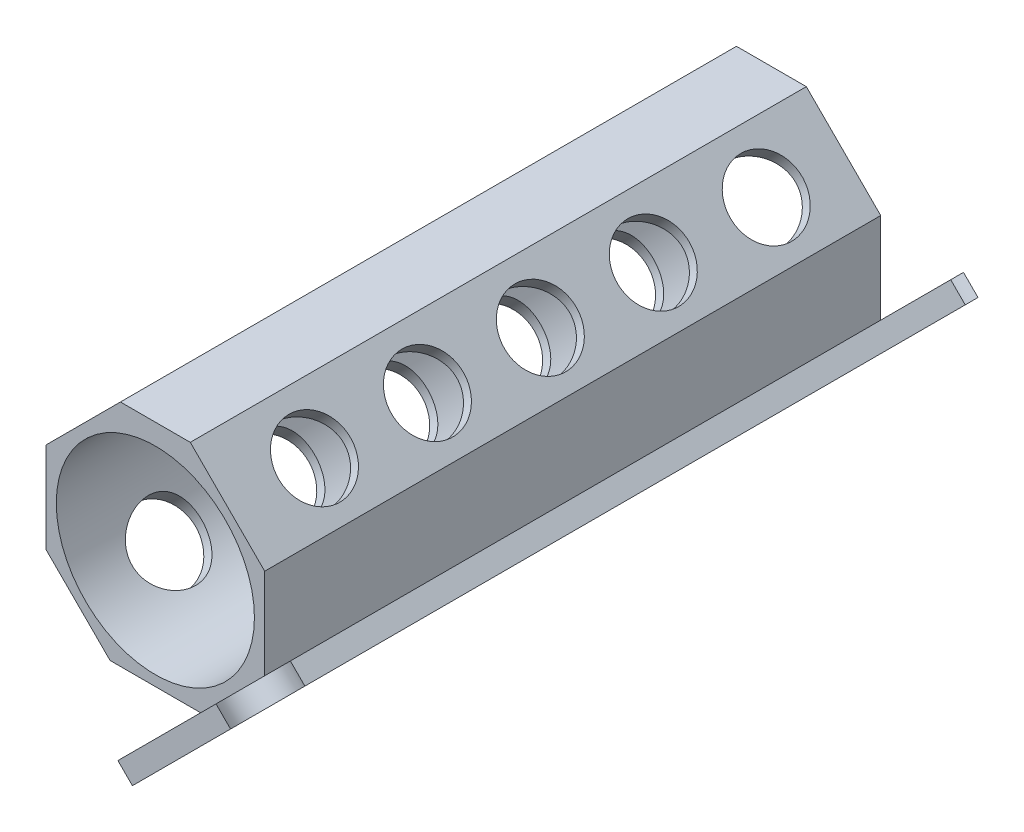
SolidWorks part; units mm, degrees
ref_plane "Ebene vorne" through (0, 0, 0) normal (1, 0, 0) x (0, 1, 0)
ref_plane "Ebene oben" through (0, 0, 0) normal (0, 0, 1) x (0, 1, 0)
ref_plane "Ebene rechts" through (0, 0, 0) normal (0, 1, 0) x (-1, 0, 0)
sketch "Skizze1" plane through (0, 0, 0) normal (0, 0, 1) x (0, 1, 0)
  line L0 (11.6589, 3.4025) -> (11.6589, -3.4025)
  line L13 (11.6589, 3.4025) -> (4.4114, 10.65)
  line L14 (4.4114, 10.65) -> (-4.4114, 10.65)
  line L15 (-4.4114, 10.65) -> (-10.65, 4.4114)
  line L16 (-10.65, 4.4114) -> (-10.65, -4.4114)
  line L17 (-10.65, -4.4114) -> (-4.4114, -10.65)
  line L18 (-4.4114, -10.65) -> (4.4114, -10.65)
  line L19 (4.4114, -10.65) -> (11.6589, -3.4025)
  line L29 (10.65, -1.6019) -> (10.65, 6.6409) [skipped]
  circle A0 centre (0, 0) radius 9.65
  circle A1 centre (0, 0) radius 10.65 construction
  dimension "D1" = 19.3
  dimension "D2" = 21.3
extrude "Aufsatz-Linear austragen1" add sketch "Skizze1" along normal blind 60
sketch "Skizze9" plane through (7.5307, 7.5307, 0) normal (0.7071, 0.7071, 0) x (-0.7071, 0.7071, 0)
  line L0 (0.7134, 60) -> (0.7134, 0) construction
  line L2 (-4.4114, 60) -> (5.8381, 60) construction
  line L3 (-4.4114, 0) -> (5.8381, 0) construction
  circle A0 centre (0.6135, 51.6) radius 3.5
  circle A1 centre (0.6135, 40.6) radius 3.5
  circle A2 centre (0.6135, 29.6) radius 3.5
  circle A3 centre (0.6135, 18.6) radius 3.5
  circle A4 centre (0.6135, 7.6) radius 3.5
  dimension "D1" = 7
  dimension "D2" = 5
extrude "Schnitt-Linear austragen8" cut sketch "Skizze9" against normal through all
sketch "Skizze13" plane through (7.5307, -7.5307, 0) normal (0.7071, -0.7071, 0) x (0.7071, 0.7071, 0)
  line L0 (0, 60) -> (0, 0) construction
  line L1 (-11, -6.4) -> (11, -6.4)
  line L2 (-11, -6.4) -> (-11, 66.4)
  line L3 (-11, 66.4) -> (11, 66.4)
  line L4 (11, -6.4) -> (11, 66.4)
  line L5 (-11, -6.4) -> (11, 66.4) construction
  line L6 (-11, 66.4) -> (11, -6.4) construction
  line L7 (-4.4114, 60) -> (4.4114, 60) construction
  point P0 (0, 30)
  point P11 (0, 30)
  dimension "D1" = 22
  dimension "D2" = 72.8
extrude "Aufsatz-Linear austragen2" add sketch "Skizze13" along normal blind 2
sketch "Skizze14" plane through (8.9449, -8.9449, 0) normal (0.7071, -0.7071, 0) x (0.7071, 0.7071, 0)
  circle A0 centre (8.88, 64.28) radius 3
  circle A2 centre (-8.88, -4.28) radius 3
  circle A3 centre (8.88, -4.28) radius 3
  circle A4 centre (-8.88, 64.28) radius 3
  dimension "D1" = 6
  dimension "D2" = 2.12
  dimension "D3" = 6
  dimension "D4" = 6
  dimension "D8" = 6
  dimension "D5" = 2.12
  dimension "D6" = 2.12
  dimension "D7" = 2.12
  dimension "D9" = 2.12
  dimension "D10" = 2.12
  dimension "D11" = 2.12
  dimension "D12" = 2.12
extrude "Schnitt-Linear austragen12" cut sketch "Skizze14" against normal blind 2
